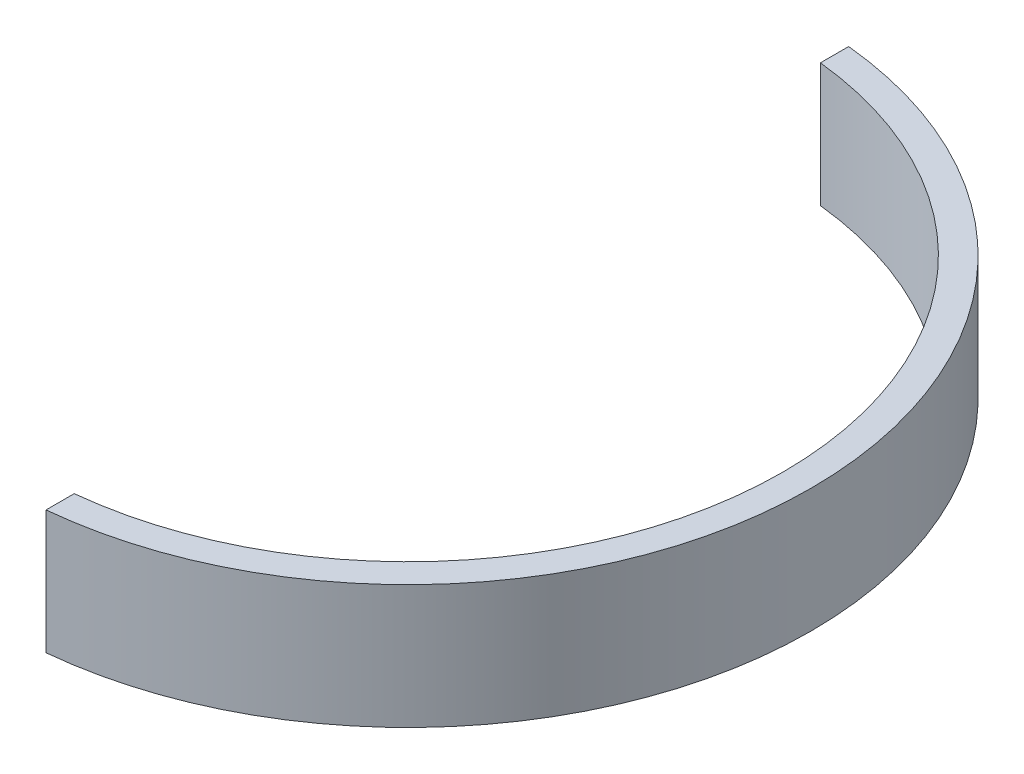
SolidWorks part; units mm, degrees
material "POLYURETHANE (11671)"
ref_plane "Front Plane" through (0, 0, 0) normal (0, 0, 1) x (1, 0, 0)
ref_plane "Top Plane" through (0, 0, 0) normal (0, 1, 0) x (1, 0, 0)
ref_plane "Right Plane" through (0, 0, 0) normal (1, 0, 0) x (0, 0, -1)
sketch "Sketch1" plane through (0, 0, 0) normal (0, 1, 0) x (1, 0, 0)
  line L0 (0, 66.845) -> (0, 71.845) construction
  line L1 (0, -71.845) -> (0, -66.845) construction
  line L2 (0, 66.845) -> (0, -66.845) construction
  line L3 (7.036, 66.4737) -> (7.036, 71.4996)
  line L4 (7.036, -66.4737) -> (7.036, -71.4996)
  arc A0 (7.036, -71.4996) -> (7.036, 71.4996) centre (0, 0) ccw
  arc A1 (7.036, -66.4737) -> (7.036, 66.4737) centre (0, 0) ccw
  arc A2 (0, -71.845) -> (7.036, -71.4996) centre (0, 0) ccw construction
  arc A3 (0, 71.845) -> (7.036, 71.4996) centre (0, 0) cw construction
  arc A4 (0, -66.845) -> (7.036, -66.4737) centre (0, 0) ccw construction
  dimension "D2" = 5
  dimension "D1" = 71.845
  dimension "D3" = 7.036
extrude "Boss-Extrude1" add sketch "Sketch1" along normal blind 22.04
ref_plane "Plane1" through (0, 11.02, 0) normal (0, 1, 0) x (1, 0, 0)
equation "\"B1\"=0.028144"
equation "\"B2\"=0.014072"
equation "\"B3\"=0.066845"
equation "\"H1\"=0.033908"
equation "\"H2\"=0.055948"
equation "\"H3\"=0.147500"
equation "\"H4\"=0.169540"
equation "\"T\"=0.005000"
equation "\"L\"=0.019701"
equation "\"bolt_hole_diameter\"=0.003400"
equation "\"spring_arm_hole_pos\"=0.007880"
equation "\"H_holes\"=0.006332"
equation "\"spring_arm_hole_max_diam\"=0.006000"
equation "\"spring_arm_hole_min_diam\"=0.003400"
equation "\"arm_hole_head_height\"=0.001650"
equation "\"D_strap\"=0.071845"
equation "\"clip_hole_D\"=0.003400"
equation "\"clip_hole_y1\"=0.007500"
equation "\"clip_hole_dist\"=0.015000"
equation "\"pad_t1\"=0.005000"
equation "\"pad_t2\"=0.000000"
equation "\"unpad_L1\"=0.067481"
equation "\"D2@Sketch1\"=\"pad_t1\"*1000"
equation "\"D1@Sketch1\"=\"D_strap\"*1000"
equation "\"D1@Boss-Extrude1\"=(\"H4\"-\"H3\")*1000"
equation "\"D3@Sketch1\"=0.5*\"B2\"*1000"
